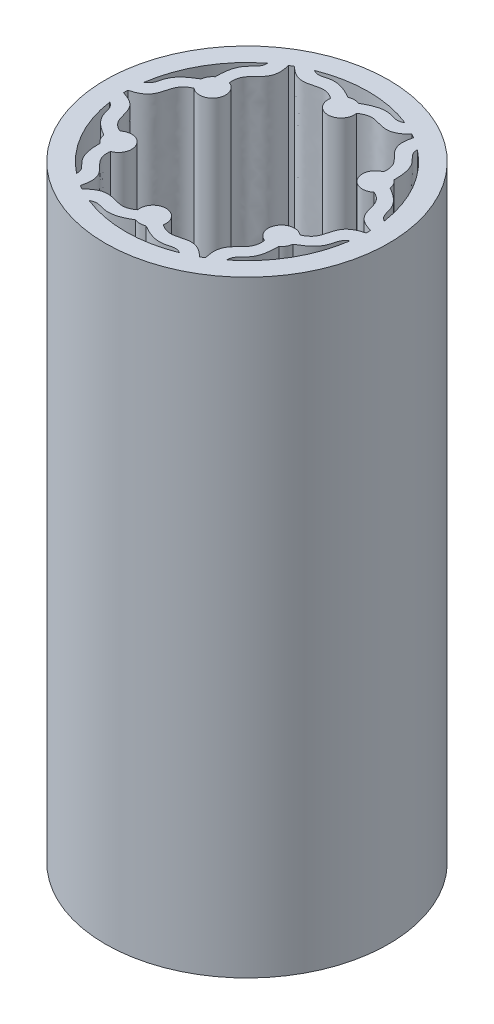
SolidWorks part; units mm, degrees
ref_plane "Front Plane" through (0, 0, 0) normal (0, 0, 1) x (1, 0, 0)
ref_plane "Top Plane" through (0, 0, 0) normal (0, 1, 0) x (1, 0, 0)
ref_plane "Right Plane" through (0, 0, 0) normal (1, 0, 0) x (0, 0, -1)
sketch "OuterShell" plane through (0, 0, 0) normal (0, 1, 0) x (1, 0, 0)
  circle A0 centre (0, 0) radius 6
  circle A1 centre (0, 0) radius 7
  dimension "D1" = 1
  dimension "D2" = 12
sketch "InnerGliders" plane through (0, 0, 0) normal (0, 1, 0) x (1, 0, 0)
  line L0 (0, 0) -> (0, 12.1496) construction
  line L1 (-2.9035, 5.2507) -> (-1.9065, 4.2412) construction
  line L2 (-1.9065, 4.2412) -> (-1.4977, 5.4129) construction
  line L3 (-1.4977, 5.4129) -> (-0.639, 4.7688) construction
  line L4 (-0.256, 5.2475) -> (-1.5371, 6.0058) construction
  line L5 (-1.5371, 6.0058) -> (-1.6739, 5.2425) construction
  line L6 (-1.6739, 5.2425) -> (-2.2371, 5.5674) construction
  line L7 (2.9035, 5.2507) -> (1.9065, 4.2412) construction
  line L8 (1.9065, 4.2412) -> (1.4977, 5.4129) construction
  line L9 (1.4977, 5.4129) -> (0.639, 4.7688) construction
  line L10 (0.256, 5.2475) -> (1.5371, 6.0058) construction
  line L11 (1.5371, 6.0058) -> (1.6739, 5.2425) construction
  line L12 (1.6739, 5.2425) -> (2.2371, 5.5674) construction
  line L13 (0, 0) -> (10.5219, 6.0748) construction
  line L14 (3.0955, 5.1399) -> (2.7197, 3.7717) construction
  line L15 (2.7197, 3.7717) -> (3.9389, 4.0035) construction
  line L16 (3.9389, 4.0035) -> (3.8104, 2.9378) construction
  line L17 (4.4165, 2.8454) -> (4.4326, 4.3341) construction
  line L18 (4.4326, 4.3341) -> (3.7032, 4.0709) construction
  line L19 (3.7032, 4.0709) -> (3.7029, 4.721) construction
  line L20 (5.999, 0.1108) -> (4.6262, 0.4695) construction
  line L21 (4.6262, 0.4695) -> (5.4365, 1.4094) construction
  line L22 (5.4365, 1.4094) -> (4.4495, 1.831) construction
  line L23 (4.6724, 2.402) -> (5.9697, 1.6717) construction
  line L24 (5.9697, 1.6717) -> (5.3771, 1.1716) construction
  line L25 (5.3771, 1.1716) -> (5.94, 0.8463) construction
  line L26 (0, 0) -> (10.5219, -6.0748) construction
  line L27 (5.999, -0.1108) -> (4.6262, -0.4695) construction
  line L28 (4.6262, -0.4695) -> (5.4365, -1.4094) construction
  line L29 (5.4365, -1.4094) -> (4.4495, -1.831) construction
  line L30 (4.6724, -2.402) -> (5.9697, -1.6717) construction
  line L31 (5.9697, -1.6717) -> (5.3771, -1.1716) construction
  line L32 (5.3771, -1.1716) -> (5.94, -0.8463) construction
  line L33 (3.0955, -5.1399) -> (2.7197, -3.7717) construction
  line L34 (2.7197, -3.7717) -> (3.9389, -4.0035) construction
  line L35 (3.9389, -4.0035) -> (3.8104, -2.9378) construction
  line L36 (4.4165, -2.8454) -> (4.4326, -4.3341) construction
  line L37 (4.4326, -4.3341) -> (3.7032, -4.0709) construction
  line L38 (3.7032, -4.0709) -> (3.7029, -4.721) construction
  line L39 (0, 0) -> (0, -12.1496) construction
  line L40 (2.9035, -5.2507) -> (1.9065, -4.2412) construction
  line L41 (1.9065, -4.2412) -> (1.4977, -5.4129) construction
  line L42 (1.4977, -5.4129) -> (0.639, -4.7688) construction
  line L43 (0.256, -5.2475) -> (1.5371, -6.0058) construction
  line L44 (1.5371, -6.0058) -> (1.6739, -5.2425) construction
  line L45 (1.6739, -5.2425) -> (2.2371, -5.5674) construction
  line L46 (-2.9035, -5.2507) -> (-1.9065, -4.2412) construction
  line L47 (-1.9065, -4.2412) -> (-1.4977, -5.4129) construction
  line L48 (-1.4977, -5.4129) -> (-0.639, -4.7688) construction
  line L49 (-0.256, -5.2475) -> (-1.5371, -6.0058) construction
  line L50 (-1.5371, -6.0058) -> (-1.6739, -5.2425) construction
  line L51 (-1.6739, -5.2425) -> (-2.2371, -5.5674) construction
  line L52 (0, 0) -> (-10.5219, -6.0748) construction
  line L53 (-3.0955, -5.1399) -> (-2.7197, -3.7717) construction
  line L54 (-2.7197, -3.7717) -> (-3.9389, -4.0035) construction
  line L55 (-3.9389, -4.0035) -> (-3.8104, -2.9378) construction
  line L56 (-4.4165, -2.8454) -> (-4.4326, -4.3341) construction
  line L57 (-4.4326, -4.3341) -> (-3.7032, -4.0709) construction
  line L58 (-3.7032, -4.0709) -> (-3.7029, -4.721) construction
  line L59 (-5.999, -0.1108) -> (-4.6262, -0.4695) construction
  line L60 (-4.6262, -0.4695) -> (-5.4365, -1.4094) construction
  line L61 (-5.4365, -1.4094) -> (-4.4495, -1.831) construction
  line L62 (-4.6724, -2.402) -> (-5.9697, -1.6717) construction
  line L63 (-5.9697, -1.6717) -> (-5.3771, -1.1716) construction
  line L64 (-5.3771, -1.1716) -> (-5.94, -0.8463) construction
  line L65 (0, 0) -> (-10.5219, 6.0748) construction
  line L66 (-5.999, 0.1108) -> (-4.6262, 0.4695) construction
  line L67 (-4.6262, 0.4695) -> (-5.4365, 1.4094) construction
  line L68 (-5.4365, 1.4094) -> (-4.4495, 1.831) construction
  line L69 (-4.6724, 2.402) -> (-5.9697, 1.6717) construction
  line L70 (-5.9697, 1.6717) -> (-5.3771, 1.1716) construction
  line L71 (-5.3771, 1.1716) -> (-5.94, 0.8463) construction
  line L72 (-3.0955, 5.1399) -> (-2.7197, 3.7717) construction
  line L73 (-2.7197, 3.7717) -> (-3.9389, 4.0035) construction
  line L74 (-3.9389, 4.0035) -> (-3.8104, 2.9378) construction
  line L75 (-4.4165, 2.8454) -> (-4.4326, 4.3341) construction
  line L76 (-4.4326, 4.3341) -> (-3.7032, 4.0709) construction
  line L77 (-3.7032, 4.0709) -> (-3.7029, 4.721) construction
  circle A0 centre (0, 0) radius 4 construction
  circle A1 centre (0, 0) radius 4.65 construction
  arc A2 (-0.639, 4.7688) -> (0.639, 4.7688) centre (0, 4.65) ccw
  circle A3 centre (0, 0) radius 6 construction
  arc A4 (-2.9035, 5.2507) -> (-2.2371, 5.5674) centre (-2.5923, 5.4554) cw
  arc A5 (2.9035, 5.2507) -> (2.2371, 5.5674) centre (2.5923, 5.4554) ccw
  arc A6 (0.256, 5.2475) -> (-0.256, 5.2475) centre (0, 4.65) ccw
  arc A7 (3.8104, 2.9378) -> (4.4495, 1.831) centre (4.027, 2.325) ccw
  arc A8 (3.0955, 5.1399) -> (3.7029, 4.721) centre (3.4283, 4.9727) cw
  arc A9 (5.999, 0.1108) -> (5.94, 0.8463) centre (6.0206, 0.4827) ccw
  arc A10 (4.6724, 2.402) -> (4.4165, 2.8454) centre (4.027, 2.325) ccw
  circle A11 centre (0, 0) radius 4 construction
  circle A12 centre (0, 0) radius 4.65 construction
  arc A13 (4.4495, -1.831) -> (3.8104, -2.9378) centre (4.027, -2.325) ccw
  arc A14 (5.999, -0.1108) -> (5.94, -0.8463) centre (6.0206, -0.4827) cw
  arc A15 (3.0955, -5.1399) -> (3.7029, -4.721) centre (3.4283, -4.9727) ccw
  arc A16 (4.4165, -2.8454) -> (4.6724, -2.402) centre (4.027, -2.325) ccw
  circle A17 centre (0, 0) radius 4 construction
  circle A18 centre (0, 0) radius 4.65 construction
  arc A19 (0.639, -4.7688) -> (-0.639, -4.7688) centre (0, -4.65) ccw
  arc A20 (2.9035, -5.2507) -> (2.2371, -5.5674) centre (2.5923, -5.4554) cw
  arc A21 (-2.9035, -5.2507) -> (-2.2371, -5.5674) centre (-2.5923, -5.4554) ccw
  arc A22 (-0.256, -5.2475) -> (0.256, -5.2475) centre (0, -4.65) ccw
  circle A23 centre (0, 0) radius 4 construction
  circle A24 centre (0, 0) radius 4.65 construction
  arc A25 (-3.8104, -2.9378) -> (-4.4495, -1.831) centre (-4.027, -2.325) ccw
  arc A26 (-3.0955, -5.1399) -> (-3.7029, -4.721) centre (-3.4283, -4.9727) cw
  arc A27 (-5.999, -0.1108) -> (-5.94, -0.8463) centre (-6.0206, -0.4827) ccw
  arc A28 (-4.6724, -2.402) -> (-4.4165, -2.8454) centre (-4.027, -2.325) ccw
  circle A29 centre (0, 0) radius 4 construction
  circle A30 centre (0, 0) radius 4.65 construction
  arc A31 (-4.4495, 1.831) -> (-3.8104, 2.9378) centre (-4.027, 2.325) ccw
  arc A32 (-5.999, 0.1108) -> (-5.94, 0.8463) centre (-6.0206, 0.4827) cw
  arc A33 (-3.0955, 5.1399) -> (-3.7029, 4.721) centre (-3.4283, 4.9727) ccw
  arc A34 (-4.4165, 2.8454) -> (-4.6724, 2.402) centre (-4.027, 2.325) ccw
  circle A35 centre (0, 0) radius 4 construction
  circle A36 centre (0, 0) radius 4.65 construction
  spline S0 degree 3 poles (-2.9035, 5.2507) (-1.9065, 4.2412) (-1.4977, 5.4129) (-0.639, 4.7688) knots 0 0 0 0 1 1 1 1
  spline S1 degree 3 poles (-0.256, 5.2475) (-1.5371, 6.0058) (-1.6739, 5.2425) (-2.2371, 5.5674) knots 0 0 0 0 1 1 1 1
  spline S2 degree 3 poles (2.9035, 5.2507) (1.9065, 4.2412) (1.4977, 5.4129) (0.639, 4.7688) knots 0 0 0 0 1 1 1 1
  spline S3 degree 3 poles (0.256, 5.2475) (1.5371, 6.0058) (1.6739, 5.2425) (2.2371, 5.5674) knots 0 0 0 0 1 1 1 1
  spline S4 degree 3 poles (3.0955, 5.1399) (2.7197, 3.7717) (3.9389, 4.0035) (3.8104, 2.9378) knots 0 0 0 0 1 1 1 1
  spline S5 degree 3 poles (4.4165, 2.8454) (4.4326, 4.3341) (3.7032, 4.0709) (3.7029, 4.721) knots 0 0 0 0 1 1 1 1
  spline S6 degree 3 poles (5.999, 0.1108) (4.6262, 0.4695) (5.4365, 1.4094) (4.4495, 1.831) knots 0 0 0 0 1 1 1 1
  spline S7 degree 3 poles (4.6724, 2.402) (5.9697, 1.6717) (5.3771, 1.1716) (5.94, 0.8463) knots 0 0 0 0 1 1 1 1
  spline S8 degree 3 poles (5.999, -0.1108) (4.6262, -0.4695) (5.4365, -1.4094) (4.4495, -1.831) knots 0 0 0 0 1 1 1 1
  spline S9 degree 3 poles (4.6724, -2.402) (5.9697, -1.6717) (5.3771, -1.1716) (5.94, -0.8463) knots 0 0 0 0 1 1 1 1
  spline S10 degree 3 poles (3.0955, -5.1399) (2.7197, -3.7717) (3.9389, -4.0035) (3.8104, -2.9378) knots 0 0 0 0 1 1 1 1
  spline S11 degree 3 poles (4.4165, -2.8454) (4.4326, -4.3341) (3.7032, -4.0709) (3.7029, -4.721) knots 0 0 0 0 1 1 1 1
  spline S12 degree 3 poles (2.9035, -5.2507) (1.9065, -4.2412) (1.4977, -5.4129) (0.639, -4.7688) knots 0 0 0 0 1 1 1 1
  spline S13 degree 3 poles (0.256, -5.2475) (1.5371, -6.0058) (1.6739, -5.2425) (2.2371, -5.5674) knots 0 0 0 0 1 1 1 1
  spline S14 degree 3 poles (-2.9035, -5.2507) (-1.9065, -4.2412) (-1.4977, -5.4129) (-0.639, -4.7688) knots 0 0 0 0 1 1 1 1
  spline S15 degree 3 poles (-0.256, -5.2475) (-1.5371, -6.0058) (-1.6739, -5.2425) (-2.2371, -5.5674) knots 0 0 0 0 1 1 1 1
  spline S16 degree 3 poles (-3.0955, -5.1399) (-2.7197, -3.7717) (-3.9389, -4.0035) (-3.8104, -2.9378) knots 0 0 0 0 1 1 1 1
  spline S17 degree 3 poles (-4.4165, -2.8454) (-4.4326, -4.3341) (-3.7032, -4.0709) (-3.7029, -4.721) knots 0 0 0 0 1 1 1 1
  spline S18 degree 3 poles (-5.999, -0.1108) (-4.6262, -0.4695) (-5.4365, -1.4094) (-4.4495, -1.831) knots 0 0 0 0 1 1 1 1
  spline S19 degree 3 poles (-4.6724, -2.402) (-5.9697, -1.6717) (-5.3771, -1.1716) (-5.94, -0.8463) knots 0 0 0 0 1 1 1 1
  spline S20 degree 3 poles (-5.999, 0.1108) (-4.6262, 0.4695) (-5.4365, 1.4094) (-4.4495, 1.831) knots 0 0 0 0 1 1 1 1
  spline S21 degree 3 poles (-4.6724, 2.402) (-5.9697, 1.6717) (-5.3771, 1.1716) (-5.94, 0.8463) knots 0 0 0 0 1 1 1 1
  spline S22 degree 3 poles (-3.0955, 5.1399) (-2.7197, 3.7717) (-3.9389, 4.0035) (-3.8104, 2.9378) knots 0 0 0 0 1 1 1 1
  spline S23 degree 3 poles (-4.4165, 2.8454) (-4.4326, 4.3341) (-3.7032, 4.0709) (-3.7029, 4.721) knots 0 0 0 0 1 1 1 1
  point P20 (0, 0)
  point P27 (-2.9035, 5.2507)
  point P28 (-1.9065, -4.2412)
  point P29 (-2.2371, 5.5674)
  point P140 (0, 0)
  point P141 (-1.6582, 6.055)
  point P142 (-1.5371, 6.0058)
  dimension "D1" = 8
  dimension "D2" = 9.3
extrude "Boss-Extrude2" add sketch "OuterShell" along normal blind 30
extrude "Boss-Extrude3" add sketch "InnerGliders" along normal blind 30
